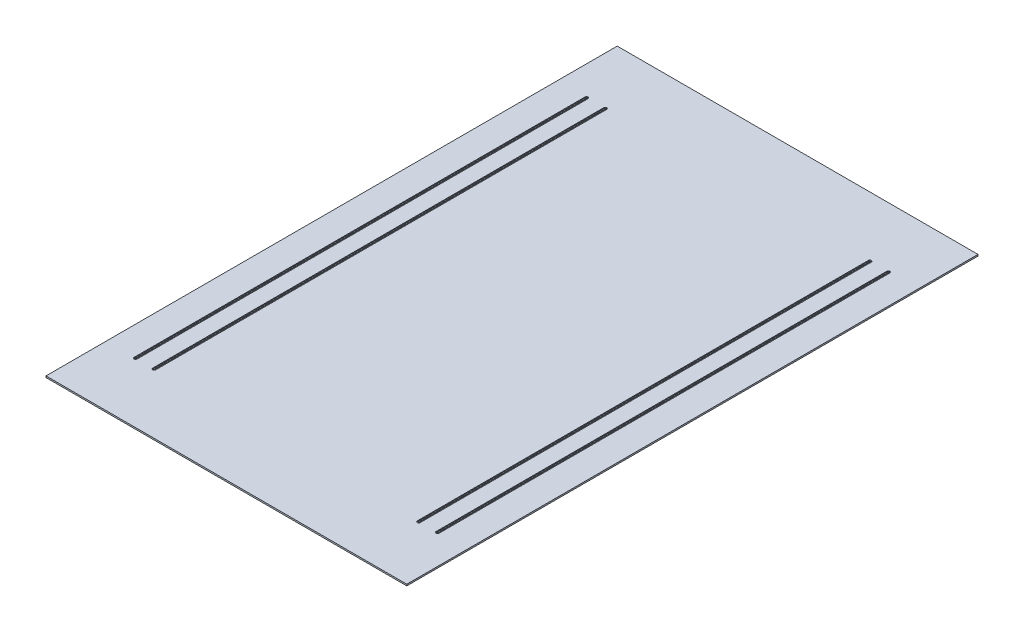
SolidWorks part; units mm, degrees
ref_plane "Front Plane" through (0, 0, 0) normal (0, 0, 1) x (1, 0, 0)
ref_plane "Top Plane" through (0, 0, 0) normal (0, 1, 0) x (1, 0, 0)
ref_plane "Right Plane" through (0, 0, 0) normal (1, 0, 0) x (0, 0, -1)
sketch "Sketch1" plane through (0, 0, 0) normal (0, 1, 0) x (1, 0, 0)
  line L1 (-600, 950) -> (600, 950)
  line L2 (-600, 950) -> (-600, -950)
  line L3 (-600, -950) -> (600, -950)
  line L4 (600, 950) -> (600, -950)
  dimension "D1" = 1900
  dimension "D2" = 1200
  dimension "D3" = 950
  dimension "D4" = 600
extrude "Boss-Extrude1" add sketch "Sketch1" along normal blind 5
sketch "Sketch2" plane through (0, 5, 0) normal (0, 1, 0) x (1, 0, 0)
  line L0 (-502, 750) -> (-502, -750) construction
  line L1 (-500, 750) -> (-500, -750)
  line L2 (-504, 750) -> (-504, -750)
  line L3 (-440, 750) -> (-440, -750) construction
  line L4 (-438, 750) -> (-438, -750)
  line L5 (-442, 750) -> (-442, -750)
  line L6 (0, 642.2099) -> (0, -657.7901) construction
  line L7 (440, 750) -> (440, -750) construction
  line L8 (438, 750) -> (438, -750)
  line L9 (442, 750) -> (442, -750)
  line L10 (502, 750) -> (502, -750) construction
  line L11 (500, 750) -> (500, -750)
  line L12 (504, 750) -> (504, -750)
  arc A0 (-500, 750) -> (-504, 750) centre (-502, 750) ccw
  arc A1 (-504, -750) -> (-500, -750) centre (-502, -750) ccw
  arc A2 (-438, 750) -> (-442, 750) centre (-440, 750) ccw
  arc A3 (-442, -750) -> (-438, -750) centre (-440, -750) ccw
  arc A4 (438, 750) -> (442, 750) centre (440, 750) cw
  arc A5 (442, -750) -> (438, -750) centre (440, -750) cw
  arc A6 (500, 750) -> (504, 750) centre (502, 750) cw
  arc A7 (504, -750) -> (500, -750) centre (502, -750) cw
  point P2 (-502, 0)
  point P11 (-440, 0)
  point P19 (440, 0)
  point P26 (502, 0)
  dimension "D3" = 2
  dimension "D1" = 1500
  dimension "D2" = 750
  dimension "D4" = 500
  dimension "D5" = 2
extrude "Cut-Extrude1" cut sketch "Sketch2" against normal blind 5
sketch "Sketch4" plane through (0, 5, 0) normal (0, 1, 0) x (1, 0, 0)
  line L0 (-435, -750) -> (-435, 750)
  line L1 (-445, 750) -> (-445, -750)
  line L2 (-438, -750) -> (-438, 750)
  line L3 (-442, 750) -> (-442, -750)
  line L4 (-438, -750) -> (-438, 750)
  line L5 (-442, 750) -> (-442, -750)
  line L6 (-500, -750) -> (-500, 750)
  line L7 (-504, 750) -> (-504, -750)
  line L8 (-500, -750) -> (-500, 750)
  line L9 (-504, 750) -> (-504, -750)
  line L10 (500, 750) -> (500, -750)
  line L11 (504, -750) -> (504, 750)
  line L12 (500, 750) -> (500, -750)
  line L13 (504, -750) -> (504, 750)
  line L14 (438, 750) -> (438, -750)
  line L15 (442, -750) -> (442, 750)
  line L16 (438, 750) -> (438, -750)
  line L17 (442, -750) -> (442, 750)
  line L18 (-497, -750) -> (-497, 750)
  line L19 (-507, 750) -> (-507, -750)
  line L20 (497, 750) -> (497, -750)
  line L21 (507, -750) -> (507, 750)
  line L22 (435, 750) -> (435, -750)
  line L23 (445, -750) -> (445, 750)
  arc A0 (-435, 750) -> (-445, 750) centre (-440, 750) ccw
  arc A1 (-445, -750) -> (-435, -750) centre (-440, -750) ccw
  arc A2 (-442, -750) -> (-438, -750) centre (-440, -750) ccw
  arc A3 (-438, 750) -> (-442, 750) centre (-440, 750) ccw
  arc A4 (-442, -750) -> (-438, -750) centre (-440, -750) ccw
  arc A5 (-438, 750) -> (-442, 750) centre (-440, 750) ccw
  arc A6 (-504, -750) -> (-500, -750) centre (-502, -750) ccw
  arc A7 (-500, 750) -> (-504, 750) centre (-502, 750) ccw
  arc A8 (-504, -750) -> (-500, -750) centre (-502, -750) ccw
  arc A9 (-500, 750) -> (-504, 750) centre (-502, 750) ccw
  arc A10 (500, -750) -> (504, -750) centre (502, -750) ccw
  arc A11 (504, 750) -> (500, 750) centre (502, 750) ccw
  arc A12 (500, -750) -> (504, -750) centre (502, -750) ccw
  arc A13 (504, 750) -> (500, 750) centre (502, 750) ccw
  arc A14 (438, -750) -> (442, -750) centre (440, -750) ccw
  arc A15 (442, 750) -> (438, 750) centre (440, 750) ccw
  arc A16 (438, -750) -> (442, -750) centre (440, -750) ccw
  arc A17 (442, 750) -> (438, 750) centre (440, 750) ccw
  arc A18 (-497, 750) -> (-507, 750) centre (-502, 750) ccw
  arc A19 (-507, -750) -> (-497, -750) centre (-502, -750) ccw
  arc A20 (497, -750) -> (507, -750) centre (502, -750) ccw
  arc A21 (507, 750) -> (497, 750) centre (502, 750) ccw
  arc A22 (435, -750) -> (445, -750) centre (440, -750) ccw
  arc A23 (445, 750) -> (435, 750) centre (440, 750) ccw
  dimension "D1" = 0
  dimension "D2" = 0
  dimension "D3" = 0
  dimension "D4" = 0
  dimension "D5" = 3
extrude "Cut-Extrude2" cut sketch "Sketch4" against normal blind 3
